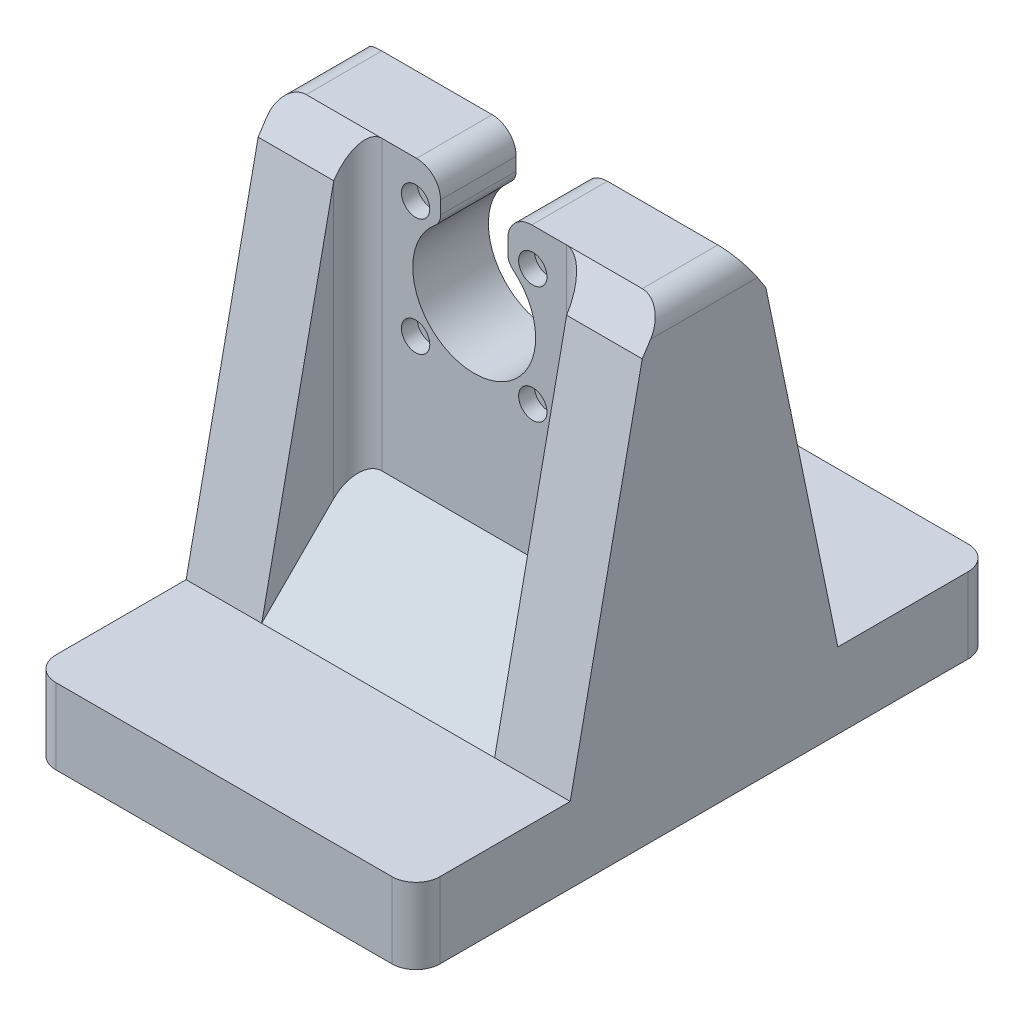
SolidWorks part; units mm, degrees
ref_plane "Front Plane" through (0, 0, 0) normal (0, 0, 1) x (1, 0, 0)
ref_plane "Top Plane" through (0, 0, 0) normal (0, 1, 0) x (1, 0, 0)
ref_plane "Right Plane" through (0, 0, 0) normal (1, 0, 0) x (0, 0, -1)
sketch "Sketch1" plane through (0, 0, 0) normal (0, 0, 1) x (1, 0, 0)
  line L0 (50.8, 25.4) -> (8.89, 25.4)
  line L2 (50.8, 25.4) -> (50.8, -76.2)
  line L3 (50.8, -76.2) -> (-50.8, -76.2)
  line L4 (-50.8, 25.4) -> (-50.8, -76.2)
  line L5 (16.9333, 25.4) -> (-50.8, -76.2) construction
  line L6 (50.8, -76.2) -> (-16.9333, 25.4) construction
  line L7 (-8.89, 25.4) -> (-50.8, 25.4)
  line L9 (-8.89, 25.4) -> (-8.89, 13.3029)
  line L10 (-8.89, 13.3029) -> (8.89, 13.3029)
  line L11 (8.89, 25.4) -> (8.89, 13.3029)
  line L12 (-50.8, -76.2) -> (-50.8, 19.05) construction
  circle A2 centre (0, 0) radius 16 construction
  point P0 (0, 0)
  point P2 (0, 25.4)
  dimension "D1" = 17.78
  dimension "D2" = 101.6
extrude "Boss-Extrude1" add sketch "Sketch1" along normal blind 20
sketch "Sketch2" plane through (0, 0, 20) normal (0, 0, 1) x (1, 0, 0)
  circle A0 centre (0, 0) radius 16.25
  circle A1 centre (-15.5, -15.5) radius 2.15
  circle A2 centre (-15.5, 15.5) radius 2.15
  circle A3 centre (15.5, -15.5) radius 2.15
  circle A4 centre (15.5, 15.5) radius 2.15
  dimension "D1" = 32.5
  dimension "D2" = 4.3
extrude "Cut-Extrude1" cut sketch "Sketch2" against normal up to surface (20 mm away) up to face at (0, -3.0243, 0)
sketch "Sketch5" plane through (0, 0, 20) normal (0, 0, 1) x (1, 0, 0)
  circle A0 centre (-15.5, 15.5) radius 3.75
  circle A1 centre (15.5, 15.5) radius 3.75
  circle A2 centre (15.5, -15.5) radius 3.75
  circle A3 centre (-15.5, -15.5) radius 3.75
  dimension "D1" = 7.5
extrude "Cut-Extrude4" cut sketch "Sketch5" against normal blind 4.2
fillet "Fillet3" radius 4 2 edges at (8.89, 13.6026, 10) (-8.89, 13.6026, 10)
sketch "Sketch6" plane through (0, -76.2, 0) normal (0, -1, 0) x (1, 0, 0)
  line L0 (-50.8, 10) -> (50.8, 10) construction
  line L1 (-50.8, 20) -> (-50.8, 0) construction
  line L2 (50.8, 20) -> (50.8, 0) construction
  line L3 (-50.8, 20) -> (50.8, 20) construction
  line L4 (-50.8, -66.2) -> (50.8, -66.2)
  line L5 (-50.8, -66.2) -> (-50.8, 86.2)
  line L6 (-50.8, 86.2) -> (50.8, 86.2)
  line L7 (50.8, -66.2) -> (50.8, 86.2)
  line L8 (-50.8, -66.2) -> (50.8, 86.2) construction
  line L9 (-50.8, 86.2) -> (50.8, -66.2) construction
  point P6 (0, 10)
  dimension "D1" = 152.4
extrude "Boss-Extrude2" add sketch "Sketch6" along normal blind 20
sketch "Sketch7" plane through (0, -96.2, 0) normal (0, -1, 0) x (1, 0, 0)
  line L0 (-50.8, 10) -> (50.8, 10) construction
  line L1 (-50.8, 86.2) -> (-50.8, -66.2) construction
  line L2 (50.8, -66.2) -> (50.8, 86.2) construction
  circle A0 centre (-38.1, 10) radius 3.75
  circle A1 centre (38.1, 10) radius 3.75
  circle A2 centre (0, 10) radius 3.75
  dimension "D3" = 7.5
  dimension "D4" = 7.5
  dimension "D1" = 12.7
  dimension "D2" = 12.7
extrude "Cut-Extrude5" cut sketch "Sketch7" against normal blind 4.2
sketch "Sketch8" plane through (0, -92, 0) normal (0, -1, 0) x (1, 0, 0)
  circle A0 centre (-38.1, 10) radius 1.8
  circle A1 centre (38.1, 10) radius 1.8
  circle A2 centre (0, 10) radius 1.8
  dimension "D1" = 3.6
extrude "Cut-Extrude6" cut sketch "Sketch8" against normal blind 60
chamfer "Chamfer1" distance 25.4 angle 45 2 edges at (0, -76.2, 20) (0, -76.2, 0)
sketch "Sketch12" plane through (50.8, 0, 0) normal (1, 0, 0) x (0, 0, -1)
  line L0 (-86.2, -76.2) -> (-20, 25.4)
  line L1 (-20, 25.4) -> (-20, -76.2)
  line L2 (-20, -76.2) -> (-86.2, -76.2)
  line L3 (-10, 25.4) -> (-10, -96.2) construction
  line L4 (-20, 25.4) -> (0, 25.4) construction
  line L5 (66.2, -96.2) -> (-86.2, -96.2) construction
  line L6 (0, -76.2) -> (66.2, -76.2)
  line L7 (66.2, -76.2) -> (0, 25.4)
  line L8 (0, 25.4) -> (0, -76.2)
extrude "Boss-Extrude4" add sketch "Sketch12" against normal blind 20
mirror "Mirror2" about plane through (0, 0, 0) normal (1, 0, 0) of "Boss-Extrude4"
fillet "Fillet4" radius 6.35 12 edges at (50.8, -86.2, -66.2) (-50.8, -86.2, -66.2) (-50.8, -86.2, 86.2) (50.8, -86.2, 86.2) (50.8, 25.4, 10) (-50.8, 25.4, 10) (8.89, 25.4, 10) (-8.89, 25.4, 10) (-30.8, -12.7, 0) (30.8, -12.7, 0) (30.8, -12.7, 20) (-30.8, -12.7, 20)
sketch "Sketch14" plane through (50.8, 0, 0) normal (1, 0, 0) x (0, 0, -1)
  line L0 (-86.2, -76.2) -> (-26.35, 15.6544)
  line L3 (-45.4, -76.2) -> (-86.2, -76.2)
  line L4 (-45.4, -76.2) -> (-26.35, 15.6544)
  point P3 (-26.9713, 14.7008)
sketch "Sketch16" plane through (-50.8, 0, 0) normal (-1, 0, 0) x (0, 0, 1)
  line L0 (-66.2, -76.2) -> (-25.4, -76.2)
  line L1 (-25.4, -76.2) -> (-6.35, 15.6544)
  line L2 (-6.35, 15.6544) -> (-66.2, -76.2)
extrude "Cut-Extrude8" cut sketch "Sketch16" against normal through all
extrude "Cut-Extrude9" cut sketch "Sketch14" against normal through all
